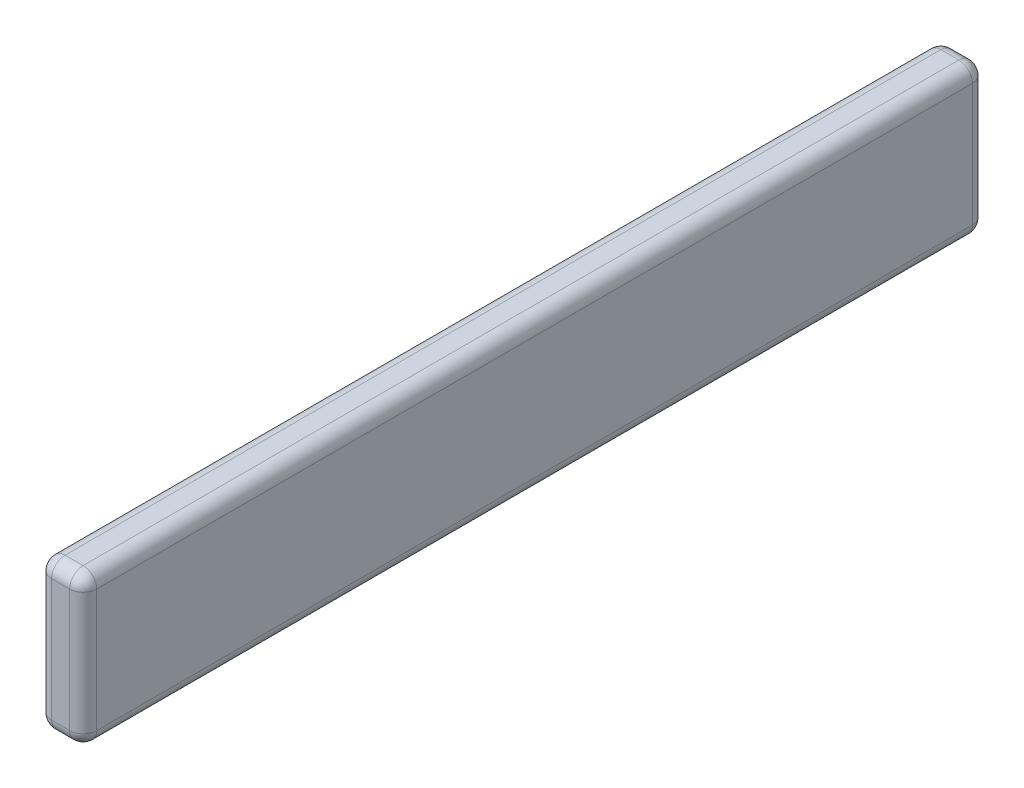
SolidWorks part; units mm, degrees
ref_plane "Front Plane" through (0, 0, 0) normal (0, 0, 1) x (1, 0, 0)
ref_plane "Top Plane" through (0, 0, 0) normal (0, 1, 0) x (1, 0, 0)
ref_plane "Right Plane" through (0, 0, 0) normal (1, 0, 0) x (0, 0, -1)
sketch "Sketch1" plane through (0, 0, 0) normal (1, 0, 0) x (0, 0, -1)
  line L1 (1000, 165.8) -> (-1000, 165.8)
  line L2 (1000, 165.8) -> (1000, -165.8)
  line L3 (1000, -165.8) -> (-1000, -165.8)
  line L4 (-1000, 165.8) -> (-1000, -165.8)
  line L5 (1000, 165.8) -> (-1000, -165.8) construction
  line L6 (1000, -165.8) -> (-1000, 165.8) construction
  point P0 (0, 0)
  dimension "D1" = 2000
  dimension "D2" = 331.6
extrude "Boss-Extrude1" add sketch "Sketch1" along normal blind 100
fillet "Fillet1" radius 30 12 edges at (50, -165.8, 1000) (50, -165.8, -1000) (50, 165.8, -1000) (50, 165.8, 1000) (0, -165.8, 0) (0, 0, -1000) (0, 165.8, 0) (0, 0, 1000) (100, 165.8, 0) (100, 0, -1000) (100, -165.8, 0) (100, 0, 1000)
